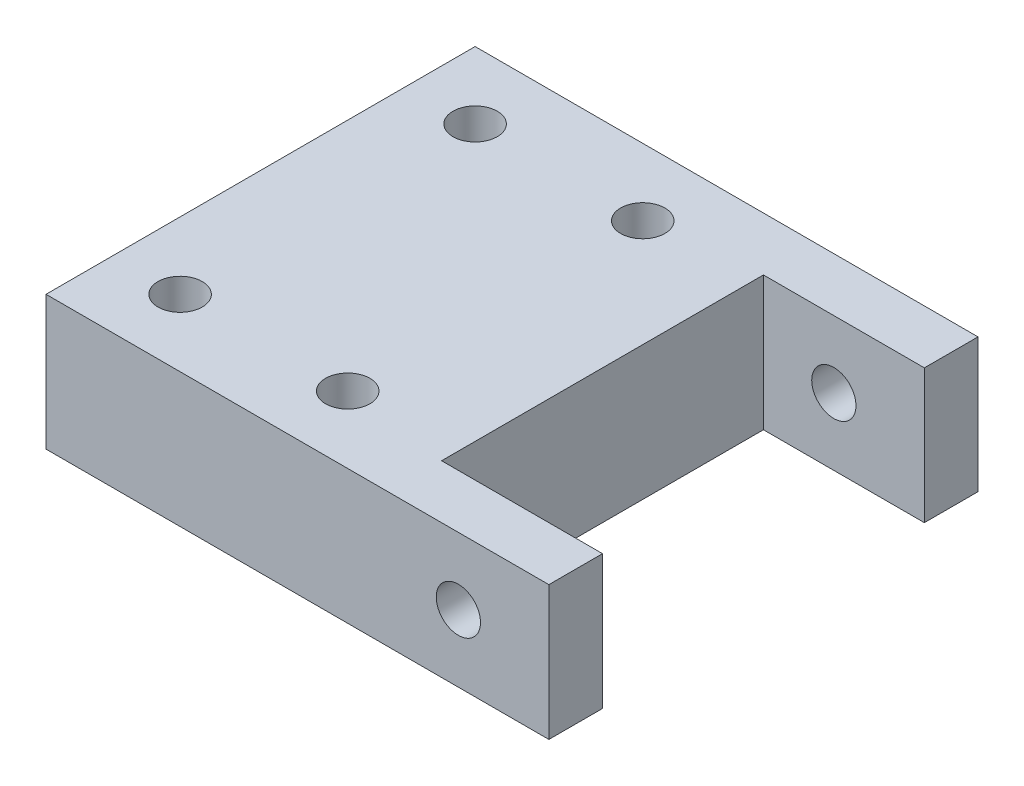
SolidWorks part; units mm, degrees
ref_plane "Alzado" through (0, 0, 0) normal (0, 0, 1) x (1, 0, 0)
ref_plane "Planta" through (0, 0, 0) normal (0, 1, 0) x (1, 0, 0)
ref_plane "Vista lateral" through (0, 0, 0) normal (1, 0, 0) x (0, 0, -1)
sketch "Croquis1" plane through (0, 0, 0) normal (0, 1, 0) x (1, 0, 0)
  line L0 (29, 13) -> (29, 0) construction
  line L1 (0, 0) -> (34, 0) construction
  line L2 (0, 0) -> (0, 13) construction
  line L3 (0, 13) -> (34, 13) construction
  line L4 (34, 0) -> (34, 13) construction
  line L5 (5, 13) -> (5, 0) construction
  line L6 (0, 6.5) -> (34, 6.5) construction
  line L7 (22.5, 13) -> (22.5, 0) construction
  line L9 (31.5, 0) -> (31.5, 13) construction
  line L10 (36, 21.5) -> (36, -8.5) construction
  line L12 (-1.5, -8.5) -> (-1.5, 21.5) construction
  line L14 (-1.5, -8.5) -> (36, -8.5) construction
  line L15 (-1.5, 21.5) -> (36, 21.5) construction
  circle A0 centre (22.5, 6.5) radius 15 construction
  circle A1 centre (22.5, 6.5) radius 6.5 construction
  circle A2 centre (16, 6.5) radius 3 construction
  circle A3 centre (22.5, 6.5) radius 12.75 construction
  circle A4 centre (2.5, 6.5) radius 1 construction
  circle A5 centre (31.5, 6.5) radius 1 construction
  dimension "D8" = 30
  dimension "D11" = 13
  dimension "D13" = 6
  dimension "D14" = 25.5
  dimension "D15" = 2
  dimension "D16" = 2
  dimension "D1" = 34
  dimension "D2" = 13
  dimension "D3" = 5
  dimension "D4" = 5
  dimension "D5" = 11.5
  dimension "D6" = 9
  dimension "D7" = 29
  dimension "D12" = 15
sketch "Croquis2" plane through (0, 0, 0) normal (0, 1, 0) x (1, 0, 0)
  line L4 (-1.5, -8.5) -> (36, -8.5) construction
  line L5 (-1.5, -8.5) -> (-1.5, 23.5)
  line L6 (36, 23.5) -> (36, -8.5)
  line L8 (-1.5, -8.5) -> (36, -8.5)
  line L9 (-1.5, 23.5) -> (36, 23.5)
  point P3 (0, 0)
  dimension "D1" = 32
  dimension "D2" = 37.5
extrude "Saliente-Extruir1" add sketch "Croquis2" along normal blind 10
sketch "Croquis7" plane through (0, 0, 0) normal (0, -1, 0) x (1, 0, 0)
  line L0 (-1.5, 8.5) -> (16.8984, 8.5)
  line L1 (-1.5, 8.5) -> (36, 8.5) construction
  line L2 (-1.5, -23.5) -> (-1.5, 8.5) construction
  line L3 (36, -23.5) -> (-1.5, -23.5) construction
  circle A0 centre (16, 3.5) radius 1.65
  circle A1 centre (3.5, 3.5) radius 1.65
  circle A2 centre (16, -18.5) radius 1.65
  circle A3 centre (3.5, -18.5) radius 1.65
  dimension "D1" = 5
  dimension "D2" = 5
  dimension "D3" = 5
  dimension "D4" = 12.5
  dimension "D5" = 12.5
  dimension "D6" = 5
  dimension "D7" = 5
sketch "Croquis13" plane through (0, 0, 8.5) normal (0, 0, 1) x (1, 0, 0)
  line L0 (-1.5, 10) -> (-1.5, 0) construction
  line L1 (36, 10) -> (36, 0) construction
  line L2 (-1.5, 10) -> (-1.5, 0) construction
  line L3 (36, 10) -> (36, 0) construction
  line L4 (-1.5, 10) -> (36, 10) construction
  line L5 (17.25, 6.7) -> (17.25, -49993.3) construction
  line L6 (35, 5) -> (-49965, 5) construction
  line L7 (-1.5, 0) -> (36, 0) construction
  line L8 (17.25, 5) -> (29.25, 5)
  circle A0 centre (29.25, 5) radius 1.65
  point P6 (17.25, 10)
  point P9 (36, 5)
  point P16 (17.25, 0)
  dimension "D1" = 12
extrude "切除-拉伸1" cut sketch "Croquis7" against normal blind 10 contours A3 | A2 | A1 | A0
extrude "切除-拉伸3" cut sketch "Croquis13" against normal blind 6 contours A0
sketch "草图6" plane through (0, 0, -23.5) normal (0, 0, -1) x (-1, 0, 0)
  line L0 (-17.25, 10) -> (-29.25, 10)
  line L1 (-36, 10) -> (1.5, 10) construction
  line L2 (-29.25, 10) -> (-29.25, 0)
  line L3 (-36, 0) -> (1.5, 0) construction
  circle A0 centre (-29.25, 5) radius 1.65
extrude "切除-拉伸4" cut sketch "草图6" against normal blind 6 contours L2 A0 | L2 A0
ref_plane "基准面1" through (36, 0, 0) normal (1, 0, 0) x (0, 0, -1)
sketch "草图7" plane through (36, 0, 0) normal (1, 0, 0) x (0, 0, -1)
  line L0 (-4.5, 10) -> (-4.5, 0)
  line L1 (-8.5, 10) -> (23.5, 10) construction
  line L2 (-8.5, 0) -> (23.5, 0) construction
  line L3 (-4.5, 0) -> (19.5, 0)
  line L4 (19.5, 0) -> (19.5, 10)
  line L5 (19.5, 10) -> (-4.5, 10)
  line L6 (-8.5, 10) -> (-8.5, 0) construction
  line L7 (23.5, 10) -> (23.5, 0) construction
  dimension "D1" = 4
  dimension "D2" = 4
extrude "切除-拉伸5" cut sketch "草图7" against normal blind 12
